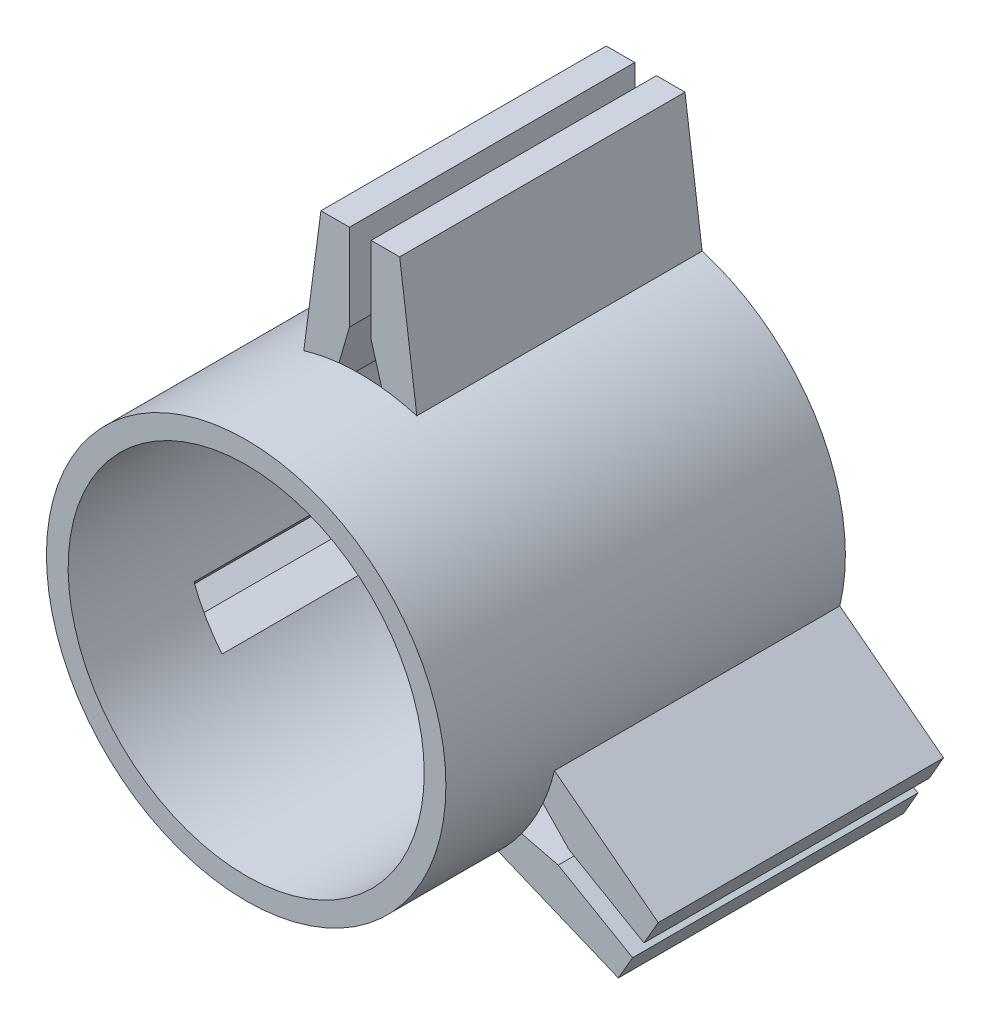
SolidWorks part; units mm, degrees
ref_plane "Front Plane" through (0, 0, 0) normal (0, 0, 1) x (1, 0, 0)
ref_plane "Top Plane" through (0, 0, 0) normal (0, 1, 0) x (1, 0, 0)
ref_plane "Right Plane" through (0, 0, 0) normal (1, 0, 0) x (0, 0, -1)
sketch "Sketch1" plane through (0, 0, 0) normal (0, 0, 1) x (1, 0, 0)
  circle A0 centre (0, 0) radius 39.624
  circle A1 centre (0, 0) radius 44.45
  dimension "D1" = 79.248
  dimension "D2" = 88.9
extrude "Boss-Extrude1" add sketch "Sketch1" along normal blind 25.4
sketch "Sketch2" plane through (0, 0, 0) normal (0, 0, -1) x (-1, 0, 0)
  line L0 (42.1209, -14.1998) -> (66.1932, -28.098)
  line L2 (2.413, 39.624) -> (2.413, 71.501)
  line L3 (2.413, 71.501) -> (8.763, 71.501)
  line L4 (8.763, 43.5777) -> (8.763, 71.501)
  line L6 (-2.413, 39.624) -> (-2.413, 71.374)
  line L7 (-2.413, 71.374) -> (-8.763, 71.374)
  line L8 (-8.763, 43.5777) -> (-8.763, 71.374)
  line L9 (63.0182, -33.5973) -> (66.1932, -28.098)
  line L10 (35.5219, -17.7223) -> (63.0182, -33.5973)
  line L11 (60.7152, -37.8402) -> (57.5402, -43.3395)
  line L12 (33.3579, -29.3778) -> (57.5402, -43.3395)
  line L13 (33.1089, -21.9017) -> (60.7152, -37.8402)
  line L14 (-33.3579, -29.3778) -> (-57.4302, -43.276)
  line L15 (-60.6052, -37.7767) -> (-57.4302, -43.276)
  line L16 (-33.1089, -21.9017) -> (-60.6052, -37.7767)
  line L17 (-63.1282, -33.6608) -> (-66.3032, -28.1615)
  line L18 (-42.1209, -14.1998) -> (-66.3032, -28.1615)
  line L19 (-35.5219, -17.7223) -> (-63.1282, -33.6608)
  line L20 (2.413, 39.624) -> (2.413, 71.501)
  line L21 (8.763, 71.501) -> (8.763, 43.5777)
  line L22 (-2.413, 39.624) -> (-2.413, 71.374)
  line L23 (-2.413, 71.374) -> (-8.763, 71.374)
  line L24 (-8.763, 43.5777) -> (-8.763, 71.374)
  arc A1 (-8.763, 43.5777) -> (-42.1209, -14.1998) centre (0, 0) ccw
  arc A2 (-33.3579, -29.3778) -> (33.3579, -29.3778) centre (0, 0) ccw
  arc A3 (42.1209, -14.1998) -> (8.763, 43.5777) centre (0, 0) ccw
  arc A6 (-2.413, 44.3845) -> (-39.6446, -20.1025) centre (0, 0) ccw
  arc A7 (39.6446, -20.1025) -> (2.413, 44.3845) centre (0, 0) ccw
  arc A8 (-37.2316, -24.2819) -> (37.2316, -24.2819) centre (0, 0) ccw
  point P29 (0, 0)
  dimension "D1" = 4.826
  dimension "D2" = 2.413
  dimension "D3" = 3
  dimension "D5" = 31.75
  dimension "D6" = 31.877
  dimension "D7" = 6.35
  dimension "D8" = 6.35
extrude "Boss-Extrude2" add sketch "Sketch2" along normal blind 63.5
sketch "Sketch3" plane through (0, 0, -63.5) normal (0, 0, -1) x (-1, 0, 0)
  line L6 (-2.413, 52.2505) -> (-2.413, 44.3845)
  line L7 (-2.413, 44.3845) -> (-2.413, 71.374) construction
  line L8 (-2.413, 52.2505) -> (-6.223, 39.1323)
  line L9 (2.413, 52.2505) -> (2.413, 44.3845)
  line L10 (2.413, 44.3845) -> (2.413, 71.501) construction
  line L11 (2.413, 52.2505) -> (6.223, 39.1323)
  line L12 (46.4567, -24.0355) -> (37.0011, -14.1769)
  line L13 (46.4567, -24.0355) -> (39.6446, -20.1025)
  line L14 (44.0437, -28.2149) -> (37.2316, -24.2819)
  line L15 (44.0437, -28.2149) -> (30.7781, -24.9554)
  line L16 (-44.0437, -28.2149) -> (-30.7781, -24.9554)
  line L17 (-44.0437, -28.2149) -> (-37.2316, -24.2819)
  line L18 (-46.4567, -24.0355) -> (-39.6446, -20.1025)
  line L19 (-46.4567, -24.0355) -> (-37.0011, -14.1769)
  circle A7 centre (0, 0) radius 39.624 construction
  arc A9 (-39.6446, -20.1025) -> (-37.2316, -24.2819) centre (0, 0) ccw
  arc A10 (2.413, 44.3845) -> (-2.413, 44.3845) centre (0, 0) ccw
  arc A11 (37.2316, -24.2819) -> (39.6446, -20.1025) centre (0, 0) ccw
  arc A12 (-37.0011, -14.1769) -> (-30.7781, -24.9554) centre (0, 0) ccw
  arc A13 (6.223, 39.1323) -> (-6.223, 39.1323) centre (0, 0) ccw
  arc A14 (30.7781, -24.9554) -> (37.0011, -14.1769) centre (0, 0) ccw
  point P20 (0, 0)
  point P30 (0, 0)
  dimension "D3" = 3.81
  dimension "D4" = 3.81
  dimension "D5" = 3
extrude "Cut-Extrude1" cut sketch "Sketch3" against normal blind 63.5
sketch "Sketch4" plane through (0, 0, -63.5) normal (0, 0, -1) x (-1, 0, 0)
  line L0 (-66.3032, -28.1615) -> (-43.2093, -10.4288)
  line L1 (-57.4302, -43.276) -> (-30.6363, -32.2059)
  line L2 (-42.1209, -14.1998) -> (-66.3032, -28.1615) construction
  line L3 (-33.3579, -29.3778) -> (-57.4302, -43.276) construction
  line L4 (-66.3032, -28.1615) -> (-42.1209, -14.1998)
  line L5 (-57.4302, -43.276) -> (-33.3579, -29.3778)
  line L6 (8.763, 71.501) -> (12.573, 42.6348)
  line L7 (8.763, 71.501) -> (8.763, 43.5777)
  line L8 (-8.763, 71.374) -> (-8.763, 43.5777)
  line L9 (-8.763, 71.374) -> (-12.573, 42.6348)
  line L10 (57.5402, -43.3395) -> (30.6363, -32.2059)
  line L11 (57.5402, -43.3395) -> (33.3579, -29.3778)
  line L12 (66.1932, -28.098) -> (42.1209, -14.1998)
  line L13 (66.1932, -28.098) -> (43.2093, -10.4288)
  arc A0 (-8.763, 43.5777) -> (-42.1209, -14.1998) centre (0, 0) ccw construction
  arc A1 (-33.3579, -29.3778) -> (33.3579, -29.3778) centre (0, 0) ccw construction
  arc A2 (-43.2093, -10.4288) -> (-42.1209, -14.1998) centre (0, 0) ccw
  arc A3 (-8.763, 43.5777) -> (-12.573, 42.6348) centre (0, 0) ccw
  arc A4 (12.573, 42.6348) -> (8.763, 43.5777) centre (0, 0) ccw
  arc A5 (42.1209, -14.1998) -> (43.2093, -10.4288) centre (0, 0) ccw
  arc A6 (30.6363, -32.2059) -> (33.3579, -29.3778) centre (0, 0) ccw
  arc A7 (-33.3579, -29.3778) -> (-30.6363, -32.2059) centre (0, 0) ccw
  point P36 (0, 0)
  dimension "D1" = 3.81
  dimension "D2" = 3.81
  dimension "D3" = 3
extrude "Boss-Extrude3" add sketch "Sketch4" against normal blind 63.5
